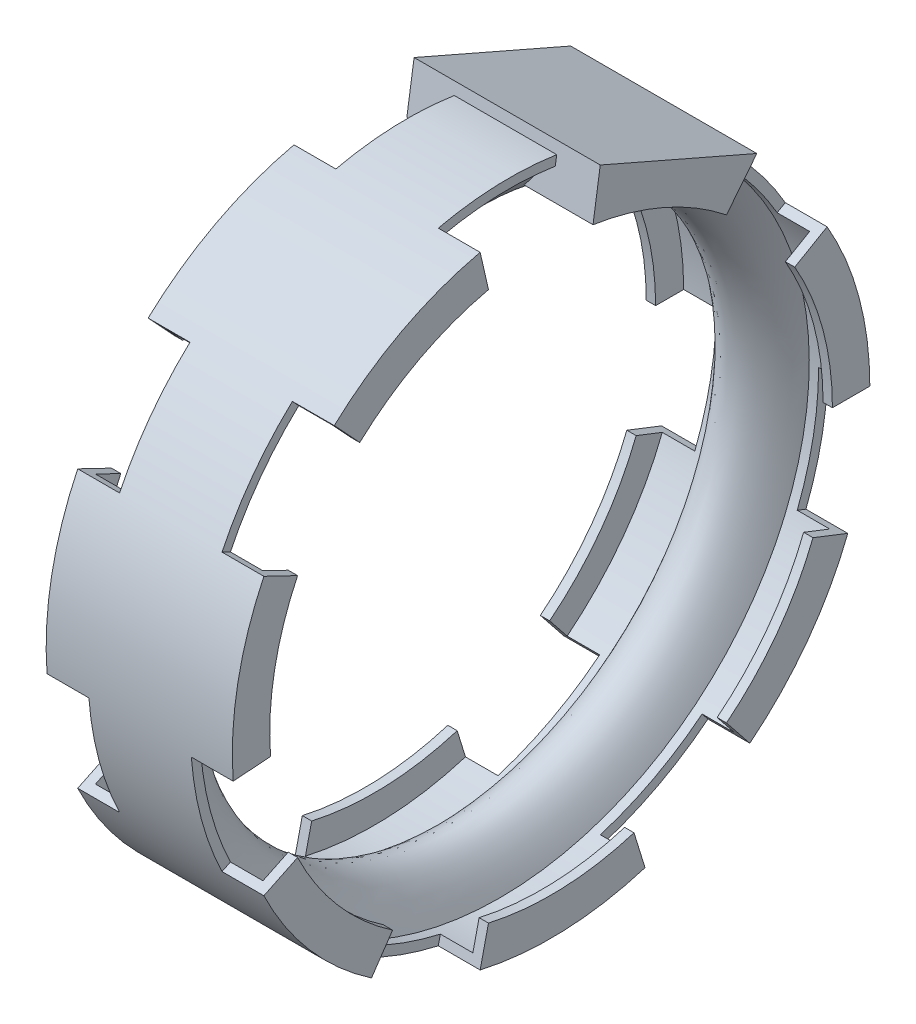
SolidWorks part; units mm, degrees
ref_plane "Front Plane" through (0, 0, 0) normal (0, 0, 1) x (1, 0, 0)
ref_plane "Top Plane" through (0, 0, 0) normal (0, 1, 0) x (1, 0, 0)
ref_plane "Right Plane" through (0, 0, 0) normal (1, 0, 0) x (0, 0, -1)
ref_plane "Plane1" through (0, 662.0435, 0) normal (0, 1, 0) x (1, 0, 0)
sketch "Sketch1" plane through (0, 662.0435, 0) normal (0, 1, 0) x (1, 0, 0)
  line L0 (-1117.5883, 38.9902) -> (-938.5883, 38.9902)
  line L1 (-938.5883, 38.9902) -> (-938.5883, 145.1376)
  line L2 (-938.5883, 145.1376) -> (-983.3383, 145.1376)
  line L3 (-1117.5883, 38.9902) -> (-1117.5883, 145.1376)
  line L4 (-1117.5883, 145.1376) -> (-1072.8383, 145.1376)
  parabola Q2 (-983.3383, 145.1376) -> (-1072.8383, 145.1376) focus (-1028.0883, 111.5751) apex (-1028.0883, 100.3876)
  parabola Q3 (-983.3383, 145.1376) -> (-1072.8383, 145.1376) focus (-1028.0883, 111.5751) apex (-1028.0883, 100.3876)
  dimension "D1" = 0
sketch "Sketch2" plane through (0, 662.0435, 0) normal (0, 1, 0) x (1, 0, 0)
  line L0 (-1117.5883, 145.1376) -> (-1117.5883, 155.1376)
  line L1 (-1117.5883, 155.1376) -> (-938.5883, 155.1376)
  line L2 (-938.5883, 155.1376) -> (-938.5883, 145.1376)
  line L3 (-1117.5883, 155.1376) -> (-1127.5883, 155.1376)
  line L4 (-1127.5883, 155.1376) -> (-1127.5883, 115.1376)
  line L5 (-1127.5883, 115.1376) -> (-1117.5883, 115.1376)
  line L6 (-1117.5883, 38.9902) -> (-1117.5883, 145.1376) construction
  line L7 (-1117.5883, 115.1376) -> (-1117.5883, 145.1376)
  line L8 (-1117.5883, 145.1376) -> (-1072.8383, 145.1376)
  line L9 (-983.3383, 145.1376) -> (-938.5883, 145.1376)
  line L10 (-938.5883, 155.1376) -> (-928.5883, 155.1376)
  line L11 (-928.5883, 155.1376) -> (-928.5883, 115.1376)
  line L12 (-928.5883, 115.1376) -> (-938.5883, 115.1376)
  line L13 (-938.5883, 38.9902) -> (-938.5883, 145.1376) construction
  line L14 (-938.5883, 115.1376) -> (-938.5883, 145.1376)
  line L15 (-1117.5883, -185.5993) -> (-938.5883, -185.5993)
  parabola Q2 (-983.3383, 145.1376) -> (-1072.8383, 145.1376) focus (-1028.0883, 111.5751) apex (-1028.0883, 100.3876)
  parabola Q3 (-983.3383, 145.1376) -> (-1072.8383, 145.1376) focus (-1028.0883, 111.5751) apex (-1028.0883, 100.3876)
  dimension "D2" = 10
  dimension "D3" = 40
  dimension "D1" = 0
sketch "Sketch3" plane through (0, 662.0435, 0) normal (0, 1, 0) x (1, 0, 0)
  line L0 (-1082.8383, 145.1376) -> (-1082.8383, 155.1376)
  line L1 (-1082.8383, 155.1376) -> (-973.3383, 155.1376)
  line L2 (-973.3383, 155.1376) -> (-973.3383, 145.1376)
  line L3 (-1117.5883, 155.1376) -> (-938.5883, 155.1376) construction
  line L4 (-1117.5883, 145.1376) -> (-1072.8383, 145.1376) construction
  line L5 (-938.5883, 145.1376) -> (-983.3383, 145.1376) construction
  line L8 (-1082.8383, 145.1376) -> (-1072.8383, 145.1376)
  line L9 (-938.5883, 145.1376) -> (-983.3383, 145.1376)
  line L10 (-973.3383, 145.1376) -> (-983.3383, 145.1376)
  parabola Q2 (-983.3383, 145.1376) -> (-1072.8383, 145.1376) focus (-1028.0883, 111.5751) apex (-1028.0883, 100.3876)
  parabola Q3 (-983.3383, 145.1376) -> (-1072.8383, 145.1376) focus (-1028.0883, 111.5751) apex (-1028.0883, 100.3876)
  dimension "D1" = 0
revolve "Revolve1" add sketch "Sketch3" angle 360 about L15
sketch "Sketch4" plane through (0, 662.0435, 0) normal (0, 1, 0) x (1, 0, 0)
  line L55 (-1072.8383, 145.1376) -> (-1117.5883, 145.1376)
  line L56 (-1117.5883, 145.1376) -> (-1117.5883, 115.1376)
  line L57 (-1117.5883, 115.1376) -> (-1127.5883, 115.1376)
  line L58 (-1127.5883, 115.1376) -> (-1127.5883, 155.1376)
  line L59 (-1127.5883, 155.1376) -> (-928.5883, 155.1376)
  line L60 (-928.5883, 155.1376) -> (-928.5883, 115.1376)
  line L61 (-928.5883, 115.1376) -> (-938.5883, 115.1376)
  line L62 (-938.5883, 115.1376) -> (-938.5883, 145.1376)
  line L63 (-938.5883, 145.1376) -> (-983.3383, 145.1376)
  parabola Q12 (-983.3383, 145.1376) -> (-1072.8383, 145.1376) focus (-1028.0883, 111.5751) apex (-1028.0883, 100.3876)
  parabola Q13 (-983.3383, 145.1376) -> (-1072.8383, 145.1376) focus (-1028.0883, 111.5751) apex (-1028.0883, 100.3876)
  dimension "D1" = 0
revolve "Revolve2" add sketch "Sketch4" angle 30 about L15
pattern_circular "CirPattern1" count 7 over 360 about axis through (0, 662.0435, 185.5993) along (1, 0, 0) of "Revolve2"
sketch "Sketch5" plane through (-928.5883, 0, 0) normal (1, 0, 0) x (0, 0, -1)
  line L0 (-140.7768, 959.4214) -> (-134.8151, 998.9746)
  line L1 (-134.8151, 998.9746) -> (-133.0236, 1010.8603)
  line L2 (1.9071, 897.169) -> (26.8467, 928.4423)
  line L3 (26.8467, 928.4423) -> (34.341, 937.8398)
  line L4 (-140.7768, 959.4214) -> (1.9071, 897.169) construction
  line L5 (-133.0236, 1010.8603) -> (34.341, 937.8398)
  arc A0 (26.8467, 928.4423) -> (-134.8151, 998.9746) centre (-185.5993, 662.0435) ccw construction
  arc A3 (1.9071, 897.169) -> (-140.7768, 959.4214) centre (-185.5993, 662.0435) ccw
  arc A4 (1.9071, 897.169) -> (-140.7768, 959.4214) centre (-185.5993, 662.0435) ccw
  dimension "D1" = 0
extrude "Boss-Extrude1" add sketch "Sketch5" against normal up to surface (199 mm away) up to face at (-1127.5883, 951.0103, 59.5243)
